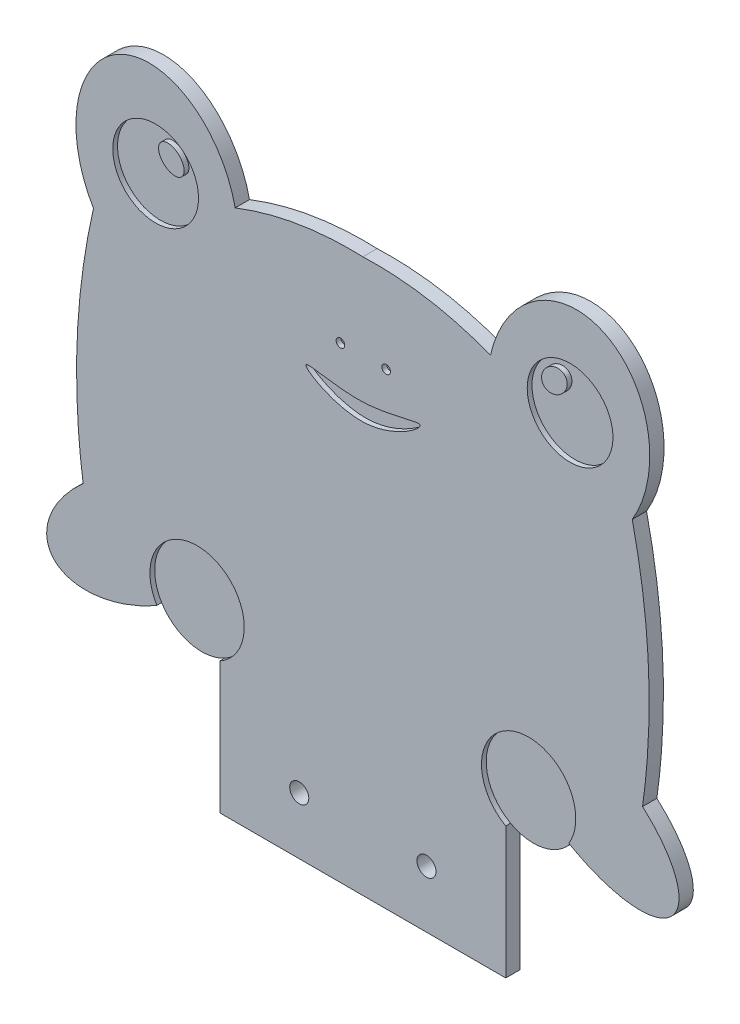
SolidWorks part; units mm, degrees
material "Acrylic (Medium-high impact)"
ref_plane "Front Plane" through (0, 0, 0) normal (0, 0, 1) x (1, 0, 0)
ref_plane "Top Plane" through (0, 0, 0) normal (0, 1, 0) x (1, 0, 0)
ref_plane "Right Plane" through (0, 0, 0) normal (1, 0, 0) x (0, 0, -1)
sketch "Sketch5" plane through (0, 0, 0) normal (0, 0, 1) x (1, 0, 0)
  line L0 (-27, -37.5) -> (-72.2903, 171.3263) construction
  line L1 (-60, 37.5) -> (60, 37.5) construction
  line L2 (-60, 37.5) -> (-60, -37.5) construction
  line L3 (-60, -37.5) -> (60, -37.5) construction
  line L4 (60, 37.5) -> (60, -37.5) construction
  line L5 (-60, 37.5) -> (60, -37.5) construction
  line L6 (-60, -37.5) -> (60, 37.5) construction
  line L7 (0, 115.2266) -> (0, -99.0086) construction
  line L9 (0, -148.6842) -> (0, 148.6842) construction
  line L10 (-30, -10.5) -> (30, -10.5)
  line L11 (-30, -10.5) -> (-30, -70.5)
  line L12 (-30, -70.5) -> (30, -70.5)
  line L13 (30, -10.5) -> (30, -70.5)
  line L14 (-30, -10.5) -> (30, -70.5) construction
  line L15 (-30, -70.5) -> (30, -10.5) construction
  circle A1 centre (-34.8, -34.2) radius 9.9
  circle A2 centre (34.8, -34.2) radius 9.9
  ellipse E0 centre (-43.2, 37.5) end of major axis (-47.7359, 58.11) minor radius 16.8
  ellipse E1 centre (-47.712, -29.82) end of major axis (-29.904, -18.69) minor radius 10.5
  ellipse E2 centre (43.2, 37.5) end of major axis (47.7359, 58.11) minor radius 16.8
  ellipse E3 centre (47.712, -29.82) end of major axis (29.904, -18.69) minor radius 10.5
  spline S0 degree 2 poles (-26.7927, 41.111) (-13.8895, 46.132) (0, 45.6) knots 0 0 0 1 1 1
  spline S1 degree 2 poles (-56.549, 26.1536) (-63.7245, -5.5446) (-56.4, -37.5) knots 0 0 0 1 1 1
  spline S2 degree 2 poles (-42.147, -38.724) (-21.1452, -41.4872) (0, -40.5) knots 0 0 0 1 1 1
  spline S3 degree 2 poles (26.7927, 41.111) (13.8895, 46.132) (0, 45.6) knots 0 0 0 1 1 1
  spline S4 degree 2 poles (42.147, -38.724) (21.1452, -41.4872) (0, -40.5) knots 0 0 0 1 1 1
  spline S5 degree 2 poles (56.549, 26.1536) (63.7245, -5.5446) (56.4, -37.5) knots 0 0 0 1 1 1
  point P0 (0, 0)
  dimension "D10" = 27.36
  dimension "D14" = 21
  dimension "D12" = 64.2
  dimension "D17" = 42.24
  dimension "D19" = 19.8
  dimension "D1" = 120
  dimension "D2" = 75
  dimension "D3" = 16.8
  dimension "D4" = 12.237
  dimension "D5" = 33
  dimension "D6" = 33.6
  dimension "D7" = 41.22
  dimension "D8" = 8.1
  dimension "D9" = 7.02
  dimension "D11" = 3.6
  dimension "D13" = 42
  dimension "D15" = 7.68
  dimension "D16" = 3
  dimension "D18" = 3.12
  dimension "D20" = 3.3
  dimension "D21" = 25.2
  dimension "D22" = 60
  dimension "D23" = 60
extrude "Boss-Extrude1" add sketch "Sketch5" along normal blind 3
sketch "Sketch6" plane through (0, 0, 3) normal (0, 0, 1) x (1, 0, 0)
  line L0 (-42.4118, 45.2268) -> (-37.9882, 41.1732) construction
  line L1 (-60, 45) -> (60, 45) construction
  line L2 (-60, 45) -> (-60, -45) construction
  line L3 (-60, -45) -> (60, -45) construction
  line L4 (60, 45) -> (60, -45) construction
  line L5 (-60, 45) -> (60, -45) construction
  line L6 (-60, -45) -> (60, 45) construction
  line L7 (0, -55) -> (0, 55) construction
  circle A0 centre (-43.5, 39) radius 9
  circle A1 centre (43.5, 39) radius 9
  ellipse E0 centre (-40.2, 43.2) end of major axis (-37.9882, 41.1732) minor radius 2.25
  ellipse E1 centre (40.2, 43.2) end of major axis (37.9882, 41.1732) minor radius 2.25
  point P2 (0, 0)
  dimension "D1" = 18
  dimension "D2" = 90
  dimension "D3" = 120
  dimension "D4" = 6
  dimension "D5" = 33
  dimension "D6" = 6
  dimension "D7" = 4.5
  dimension "D8" = 42.5
  dimension "D9" = 19.8
  dimension "D10" = 1.8
extrude "Cut-Extrude1" cut sketch "Sketch6" against normal blind 1 contours A0 | A1 | E1 | E0
sketch "Sketch8" plane through (0, 0, 3) normal (0, 0, 1) x (1, 0, 0)
  circle A0 centre (-4.7071, 27.5997) radius 0.9
  circle A1 centre (4.8929, 27.5997) radius 0.9
  spline S0 degree 3 poles (0.3368, 11.5254) (-18.0934, 22.7345) (0.1675, 17.134) (17.9164, 24.2247) (0.3368, 11.5254) (-18.0934, 22.7345) (0.1675, 17.134) knots -0.757913 -0.517799 -0.25665 0 0.242087 0.482201 0.74335 1 1.242087 1.482201 1.74335 only from (-11.9792, 20) to (-11.9792, 20)
  dimension "D9" = 1.8
  dimension "D11" = 1.8
  dimension "D1" = 19.2
  dimension "D2" = 15.6
  dimension "D3" = 24
  dimension "D4" = 20
  dimension "D5" = 12
  dimension "D6" = 3.6
  dimension "D7" = 12.12
  dimension "D8" = 5.4
  dimension "D10" = 12
  dimension "D12" = 12
  dimension "D13" = 4.8
  dimension "D14" = 4.8
extrude "Cut-Extrude2" cut sketch "Sketch8" against normal blind 1
sketch "Sketch9" plane through (0, 0, 3) normal (0, 0, 1) x (1, 0, 0)
  line L0 (0, -1.65) -> (0, 1.65) construction
  circle A0 centre (-34.8, -34.2) radius 9.9
  arc A1 (-43.2357, -39.3817) -> (-30, -42.8585) centre (-34.8, -34.2) ccw construction
  circle A2 centre (34.8, -34.2) radius 9.9
  dimension "D1" = 19.8
extrude "Cut-Extrude3" cut sketch "Sketch9" against normal blind 1
sketch "Sketch11" plane through (0, 0, 3) normal (0, 0, 1) x (1, 0, 0)
  line L0 (-30, -70.5) -> (30, -70.5) construction
  line L1 (-30, -42.8585) -> (-30, -70.5) construction
  circle A0 centre (-13.35, -58.5) radius 2
  circle A1 centre (13.35, -58.5) radius 2
  dimension "D1" = 4
  dimension "D2" = 4
  dimension "D3" = 12
  dimension "D4" = 12
  dimension "D5" = 26.7
  dimension "D6" = 16.65
extrude "Cut-Extrude4" cut sketch "Sketch11" against normal through all
